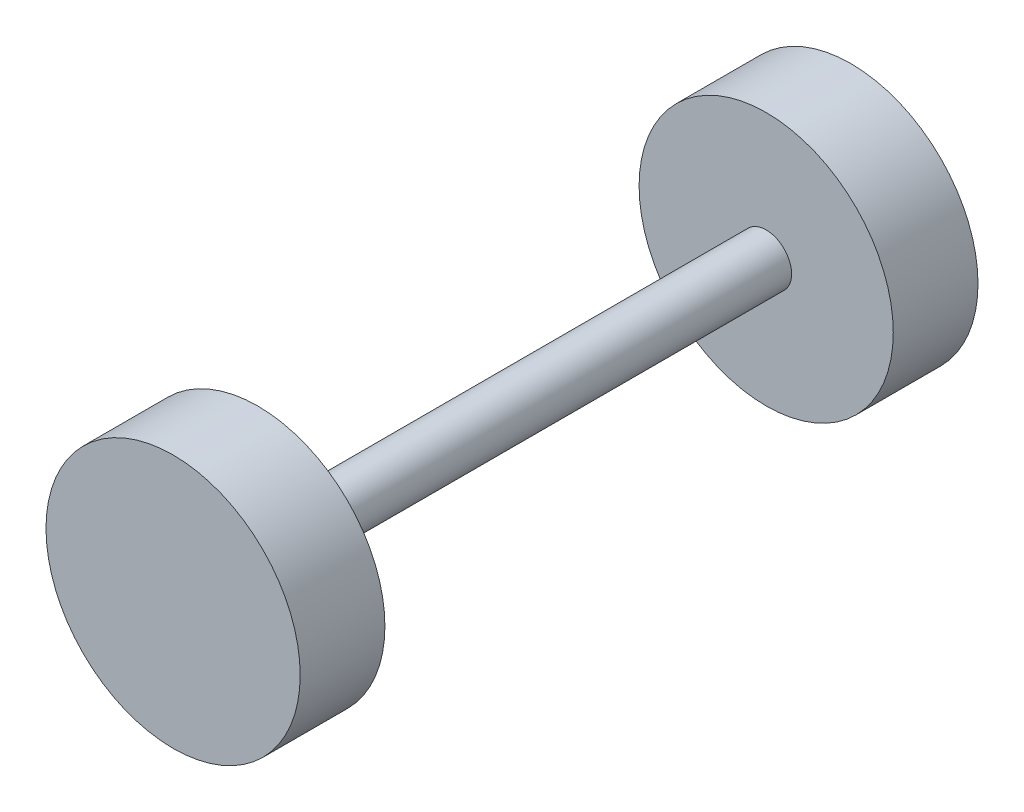
SolidWorks part; units mm, degrees
ref_plane "Plan de face" through (0, 0, 0) normal (0, 0, 1) x (1, 0, 0)
ref_plane "Plan de dessus" through (0, 0, 0) normal (0, 1, 0) x (1, 0, 0)
ref_plane "Plan de droite" through (0, 0, 0) normal (1, 0, 0) x (0, 0, -1)
sketch "Esquisse1" plane through (0, 0, 0) normal (0, 0, 1) x (1, 0, 0)
  circle A0 centre (0, 0) radius 7.5
  dimension "D1" = 15
extrude "Boss.-Extru.1" add sketch "Esquisse1" along normal blind 5
sketch "Esquisse2" plane through (0, 0, 5) normal (0, 0, 1) x (1, 0, 0)
  circle A0 centre (0, 0) radius 1.5
  dimension "D1" = 3
extrude "Boss.-Extru.2" add sketch "Esquisse2" along normal blind 30
sketch "Esquisse3" plane through (0, 0, 35) normal (0, 0, 1) x (1, 0, 0)
  circle A0 centre (0, 0) radius 7.5
extrude "Boss.-Extru.3" add sketch "Esquisse3" along normal blind 5
